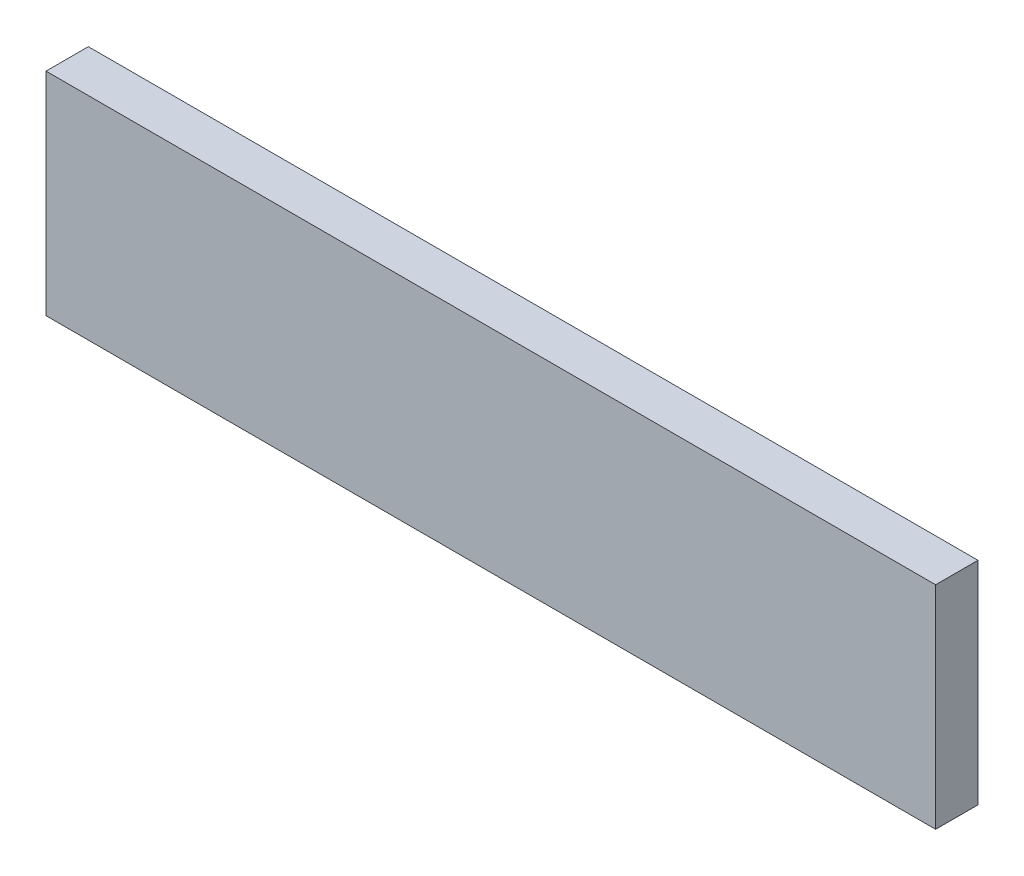
SolidWorks part; units mm, degrees
ref_plane "前视基准面" through (0, 0, 0) normal (0, 0, 1) x (1, 0, 0)
ref_plane "上视基准面" through (0, 0, 0) normal (0, 1, 0) x (1, 0, 0)
ref_plane "右视基准面" through (0, 0, 0) normal (1, 0, 0) x (0, 0, -1)
sketch "草图1" plane through (0, 0, 0) normal (0, 1, 0) x (1, 0, 0)
  line L1 (0, 0) -> (420, 0)
  line L2 (0, 0) -> (0, -20)
  line L3 (0, -20) -> (420, -20)
  line L4 (420, 0) -> (420, -20)
  dimension "D1" = 420
  dimension "D2" = 20
extrude "凸台-拉伸1" add sketch "草图1" along normal blind 100
